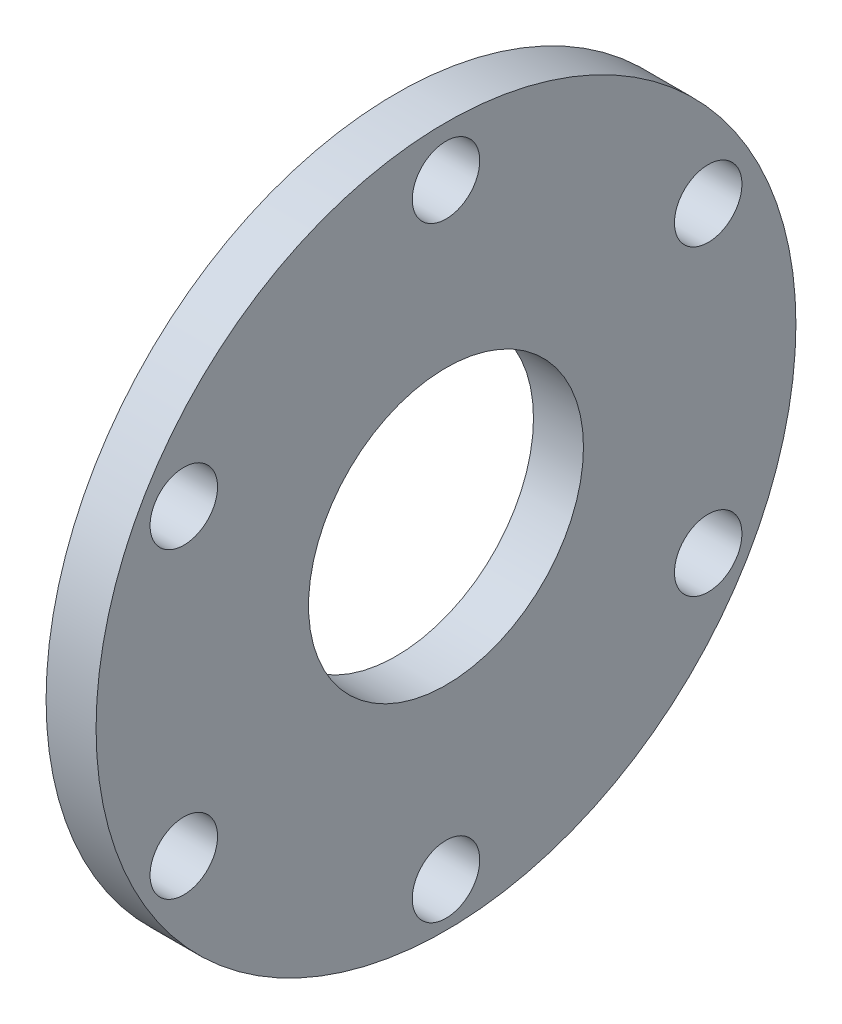
SolidWorks part; units mm, degrees
ref_plane "Alzado" through (0, 0, 0) normal (0, 0, 1) x (1, 0, 0)
ref_plane "Planta" through (0, 0, 0) normal (0, 1, 0) x (1, 0, 0)
ref_plane "Vista lateral" through (0, 0, 0) normal (1, 0, 0) x (0, 0, -1)
sketch "Croquis1" plane through (0, 0, 0) normal (1, 0, 0) x (0, 0, -1)
  circle A0 centre (0, 0) radius 70
  dimension "D1" = 140
extrude "Saliente-Extruir1" add sketch "Croquis1" along normal blind 10
sketch "Croquis2" plane through (10, 0, 0) normal (1, 0, 0) x (0, 0, -1)
  circle A0 centre (0, 0) radius 60
  dimension "D1" = 120
sketch "Croquis7" plane through (10, 0, 0) normal (1, 0, 0) x (0, 0, -1)
  line L0 (0, 0) -> (0, 82.9568)
hole_wizard "Taladro de margen para M122" positions "Croquis3D2" profile "Croquis8" hole size "M12" standard "Ansi Metric"
sketch3d "Croquis3D2"
  line L0 (10, 0, 0) -> (10, 82.9568, 0) construction
  circle A0 centre (10, 0, 0) radius 60 construction
  point P0 (10, 60, 0)
  point P4 (70, 0, 0)
sketch "Croquis8" plane through (10, 60, 0) normal (0, 1, 0) x (0, 0, -1)
  line L0 (0, 0) -> (0, 47.5558)
  line L1 (0, 47.5558) -> (6.75, 43.5)
  line L2 (6.75, 43.5) -> (6.75, 0)
  line L5 (6.75, 0) -> (0, 0)
  line L10 (0, 47.5558) -> (-6.75, 43.5) construction
  line L11 (0, -6.35) -> (0, 107.95) construction
  dimension "Diámetro de taladro" = 13.5
  dimension "Profundidad de taladro" = 43.5
  dimension "Ángulo de perforador" = 118
pattern_circular "MatrizC5" count 6 over 360 about axis through (0, -0.5631, 0) along (1, 0, 0) of "Taladro de margen para M122"
sketch "Croquis9" plane through (10, 0, 0) normal (1, 0, 0) x (0, 0, -1)
  circle A0 centre (0, 0) radius 27.5
  dimension "D1" = 55
extrude "Cortar-Extruir1" cut sketch "Croquis9" against normal blind 10
